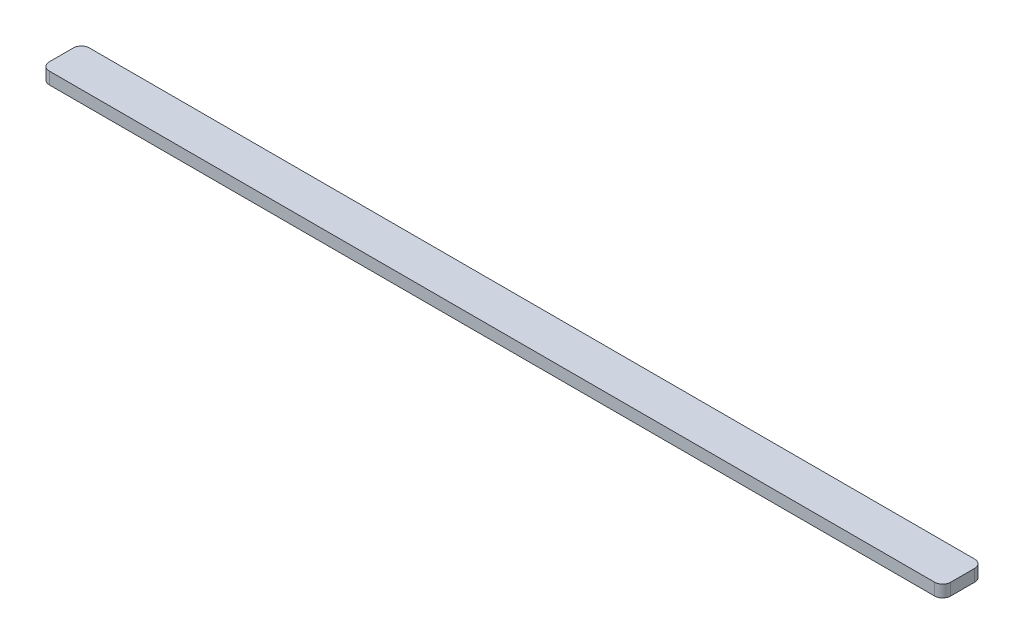
SolidWorks part; units mm, degrees
ref_plane "정면" through (0, 0, 0) normal (0, 0, 1) x (1, 0, 0)
ref_plane "윗면" through (0, 0, 0) normal (0, 1, 0) x (1, 0, 0)
ref_plane "우측면" through (0, 0, 0) normal (1, 0, 0) x (0, 0, -1)
sketch "스케치1" plane through (0, 0, 0) normal (0, 1, 0) x (1, 0, 0)
  line L1 (0, 0) -> (225, 0)
  line L2 (0, 0) -> (0, 10)
  line L3 (0, 10) -> (225, 10)
  line L4 (225, 0) -> (225, 10)
  dimension "D1" = 225
  dimension "D2" = 10
extrude "보스-돌출1" add sketch "스케치1" along normal blind 3
fillet "필렛1" radius 2 4 edges at (0, 1.5, 0) (0, 1.5, -10) (225, 1.5, -10) (225, 1.5, 0)
